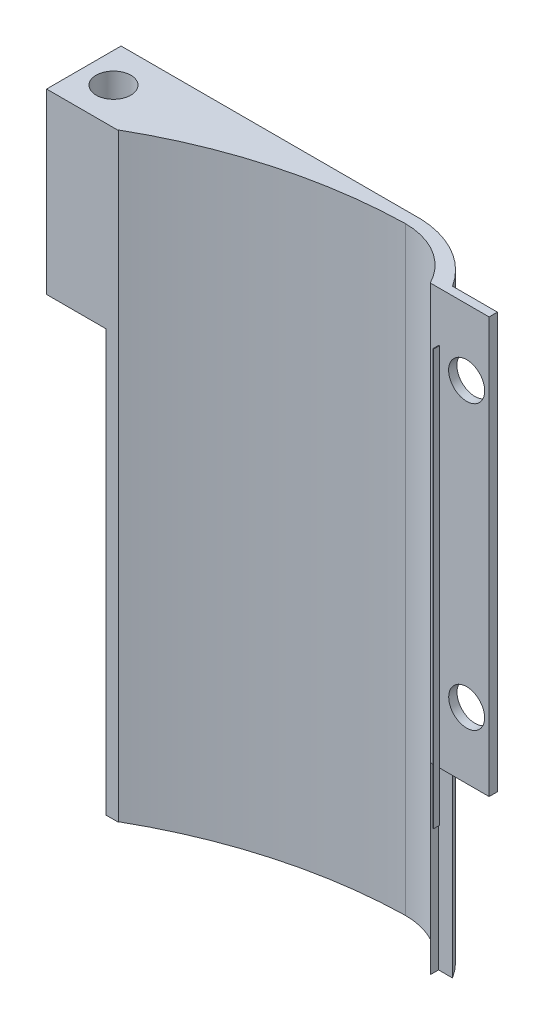
SolidWorks part; units mm, degrees
ref_plane "Front Plane" through (0, 0, 0) normal (0, 0, 1) x (1, 0, 0)
ref_plane "Top Plane" through (0, 0, 0) normal (0, 1, 0) x (1, 0, 0)
ref_plane "Right Plane" through (0, 0, 0) normal (1, 0, 0) x (0, 0, -1)
sketch "Sketch1" plane through (0, 0, 0) normal (0, 1, 0) x (1, 0, 0)
  line L1 (0, 0) -> (67.3209, 0)
  line L2 (0, 0) -> (0, -31.7448)
  line L3 (0, -31.7448) -> (67.3209, -31.7448)
  line L4 (67.3209, 0) -> (67.3209, -31.7448)
extrude "Boss-Extrude1" add sketch "Sketch1" along normal blind 127 and the other way blind 1.27 contours L2 L1 L4 L3
sketch "Sketch2" plane through (0, 127, 0) normal (0, 1, 0) x (1, 0, 0)
  line L0 (0, 0) -> (-12.6918, 0)
  line L1 (-12.6918, 0) -> (-12.6918, -31.893)
  line L2 (-12.6918, -31.893) -> (0, -31.7448)
  line L3 (0, -31.7448) -> (0, 0)
extrude "Boss-Extrude2" add sketch "Sketch2" against normal blind 38.1 contours L3 L0 L1 L2
sketch "Sketch3" plane through (0, 127, 0) normal (0, 1, 0) x (1, 0, 0)
  line L0 (-12.6918, -15.9465) -> (0, -15.9465)
  line L1 (-12.6918, 0) -> (-12.6918, -31.893) construction
  circle A0 centre (-6.3459, -23.9198) radius 3.7987
extrude "Cut-Extrude1" cut sketch "Sketch3" against normal blind 53.34 contours A0
sketch "Sketch4" plane through (0, 127, 0) normal (0, 1, 0) x (1, 0, 0)
  line L8 (-17.7261, 1.0229) -> (-17.6101, 1.0229)
  circle A0 centre (-6.2389, -8.0749) radius 3.713
extrude "Cut-Extrude2" cut sketch "Sketch4" against normal blind 72.898 contours A0
sketch "Sketch5" plane through (0, 127, 0) normal (0, 1, 0) x (1, 0, 0)
  line L0 (0, 0) -> (0, -31.7448)
  line L1 (67.3209, -15.8724) -> (67.3209, -12.0147)
  line L2 (67.3209, 0) -> (67.3209, -31.7448) construction
  line L3 (67.3209, -12.0147) -> (73.78, -12.0147)
  line L4 (73.78, -12.0147) -> (73.78, -19.5366)
  line L5 (73.78, -19.5366) -> (67.3209, -19.5366)
  line L6 (67.3209, -19.5366) -> (67.3209, -15.8724)
  line L7 (0, 0) -> (50.6455, 0)
  line L8 (-12.6918, 0) -> (67.3209, 0) construction
  line L10 (0, -31.7448) -> (67.3209, -31.7448) construction
  line L13 (67.3209, -12.0147) -> (64.8844, -12.0147)
  line L14 (67.3209, -19.5366) -> (64.8844, -19.5366)
  arc A0 (0, -15.8724) -> (50.6455, 0) centre (52.5014, -94.6574) cw
  arc A1 (50.6455, 0) -> (67.3209, -12.0147) centre (50.4446, -17.8583) cw
  arc A2 (50.6455, -31.7448) -> (67.3209, -19.5366) centre (52.8791, -17.303) ccw
  arc A3 (0, -15.8724) -> (50.6455, -31.7448) centre (47.9417, 48.3637) ccw
  arc A4 (2.546, -15.8724) -> (50.6455, -2.4899) centre (52.8779, -103.6444) cw
  arc A5 (2.546, -15.8724) -> (50.6455, -29.1917) centre (46.6879, 50.0262) ccw
  arc A6 (50.6455, -29.1917) -> (64.8844, -19.5366) centre (52.9374, -17.2447) ccw
  arc A7 (50.6455, -2.4899) -> (64.8844, -12.0147) centre (50.6631, -17.8691) cw
  arc A8 (64.8844, -12.0147) -> (64.8844, -19.5366) centre (49.5065, -15.7757) cw
extrude "Cut-Extrude3" cut sketch "Sketch5" against normal blind 177.8 contours A8 A7 A4 A5 A6
sketch "Sketch6" plane through (0, 127, 0) normal (0, 1, 0) x (1, 0, 0)
  line L1 (67.3209, 0) -> (67.3209, -31.7448) construction
  line L2 (64.3382, -15.8724) -> (64.3382, -22.7479)
  line L3 (64.3382, -22.7479) -> (67.3209, -22.7479)
  line L4 (67.3209, -22.7479) -> (67.3209, -9.0547)
  line L5 (67.3209, -9.0547) -> (64.3382, -9.0547)
  line L6 (64.3382, -9.0547) -> (64.3382, -15.8724)
extrude "Cut-Extrude4" cut sketch "Sketch6" against normal blind 140.7527 contours L2 L3 L4 L5 L6
sketch "Sketch7" plane through (0, 127, 0) normal (0, 1, 0) x (1, 0, 0)
  line L0 (64.3382, -9.0547) -> (64.3382, -10.8326)
  line L1 (64.3382, -10.8326) -> (76.9364, -10.8326)
  line L2 (76.9364, -10.8326) -> (76.9364, -9.0547)
  line L3 (76.9364, -9.0547) -> (64.3382, -9.0547)
extrude "Boss-Extrude3" add sketch "Sketch7" against normal blind 88.9367
sketch "Sketch8" plane through (0, 127, 0) normal (0, 1, 0) x (1, 0, 0)
  line L0 (64.3382, -22.7479) -> (64.3382, -21.4881)
  line L1 (64.3382, -21.4881) -> (76.96, -21.4881)
  line L2 (76.96, -21.4881) -> (76.96, -22.7479)
  line L3 (76.96, -22.7479) -> (64.3382, -22.7479)
extrude "Boss-Extrude4" add sketch "Sketch8" against normal blind 88.9367
sketch "Sketch9" plane through (0, 0, 9.0547) normal (0, 0, -1) x (-1, 0, 0)
  circle A0 centre (-72.1287, 112.8052) radius 3.8624
extrude "Cut-Extrude5" cut sketch "Sketch9" against normal blind 31.2787
sketch "Sketch10" plane through (0, 0, 9.0547) normal (0, 0, -1) x (-1, 0, 0)
  line L0 (-72.1287, 112.8052) -> (-72.1287, 127)
  line L1 (-76.9364, 127) -> (-67.3209, 127) construction
  circle A0 centre (-72.1287, 52.199) radius 3.842
extrude "Cut-Extrude6" cut sketch "Sketch10" against normal blind 32.5487 contours A0
sketch "Sketch11" plane through (0, 127, 0) normal (0, 1, 0) x (1, 0, 0)
  line L0 (-12.6918, -15.9465) -> (76.801, -15.9465)
  line L1 (-12.6918, 0) -> (-12.6918, -31.893) construction
  line L2 (76.801, -15.9465) -> (76.801, -31.893)
  line L3 (76.801, -31.893) -> (-12.6918, -31.893)
  line L4 (-12.6918, -31.893) -> (-12.6918, -15.9465)
sketch "Sketch12" plane through (0, 127, 0) normal (0, 1, 0) x (1, 0, 0)
  line L0 (-12.6918, -15.9465) -> (76.801, -15.9465)
  line L1 (76.801, -15.9465) -> (76.801, -32.8513)
  line L2 (76.801, -32.8513) -> (-12.6918, -32.8513)
  line L3 (-12.6918, -32.8513) -> (-12.6918, -15.9465)
extrude "Cut-Extrude7" cut sketch "Sketch12" against normal blind 138.176 contours L3 L0 L1 L2
sketch "Sketch13" plane through (0, 88.9, 0) normal (0, -1, 0) x (1, 0, 0)
  line L1 (0, 8.0749) -> (-3.1195, 13.478)
  line L2 (-3.1195, 13.478) -> (-9.3584, 13.478)
  line L3 (-9.3584, 13.478) -> (-12.4779, 8.0749)
  line L4 (-12.4779, 8.0749) -> (-9.3584, 2.6719)
  line L5 (-9.3584, 2.6719) -> (-3.1195, 2.6719)
  line L6 (-3.1195, 2.6719) -> (0, 8.0749)
  circle A0 centre (-6.2389, 8.0749) radius 5.4031 construction
extrude "Cut-Extrude8" cut sketch "Sketch13" against normal blind 2.54
sketch "Sketch14" plane through (0, 127, 0) normal (0, 1, 0) x (1, 0, 0)
  line L0 (-12.6918, 0) -> (67.3209, 0) construction
  line L2 (64.3382, -10.8326) -> (67.3209, -10.8326)
  line L3 (64.3382, -10.8326) -> (76.9364, -10.8326) construction
  line L5 (51.591, 0) -> (67.3209, 0)
  line L6 (67.3209, 0) -> (67.3209, -9.0547)
  arc A0 (67.3209, -9.0547) -> (51.591, 0) centre (50.8037, -19.5581) ccw
  line M9 (67.3209, -9.0547) -> (67.3209, 0)
  line M10 (67.3209, 0) -> (-12.6918, 0)
extrude "Cut-Extrude9" cut sketch "Sketch14" against normal blind 132.08 contours A0 M9 M10
